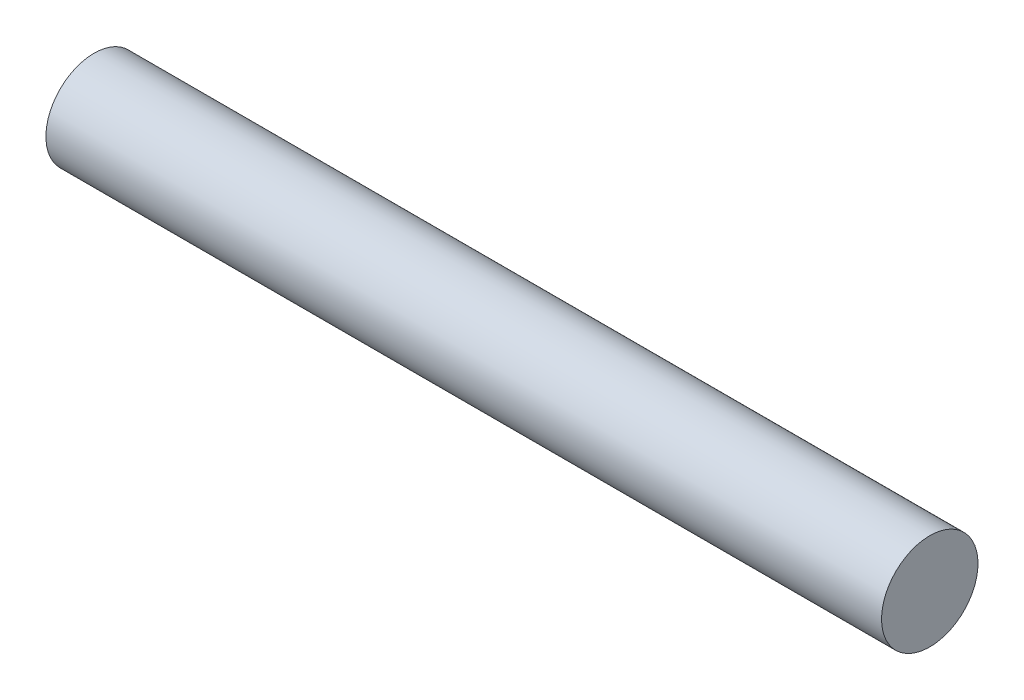
SolidWorks part; units mm, degrees
ref_plane "Frontal" through (0, 0, 0) normal (0, 0, 1) x (1, 0, 0)
ref_plane "Superior" through (0, 0, 0) normal (0, 1, 0) x (1, 0, 0)
ref_plane "Lateral" through (0, 0, 0) normal (1, 0, 0) x (0, 0, -1)
sketch "Sketch2" plane through (0, 0, 0) normal (1, 0, 0) x (0, 0, -1)
  circle A0 centre (0, 0) radius 3.75
  dimension "D1" = 7.5
extrude "Base-Extrude" add sketch "Sketch2" along normal blind 65
